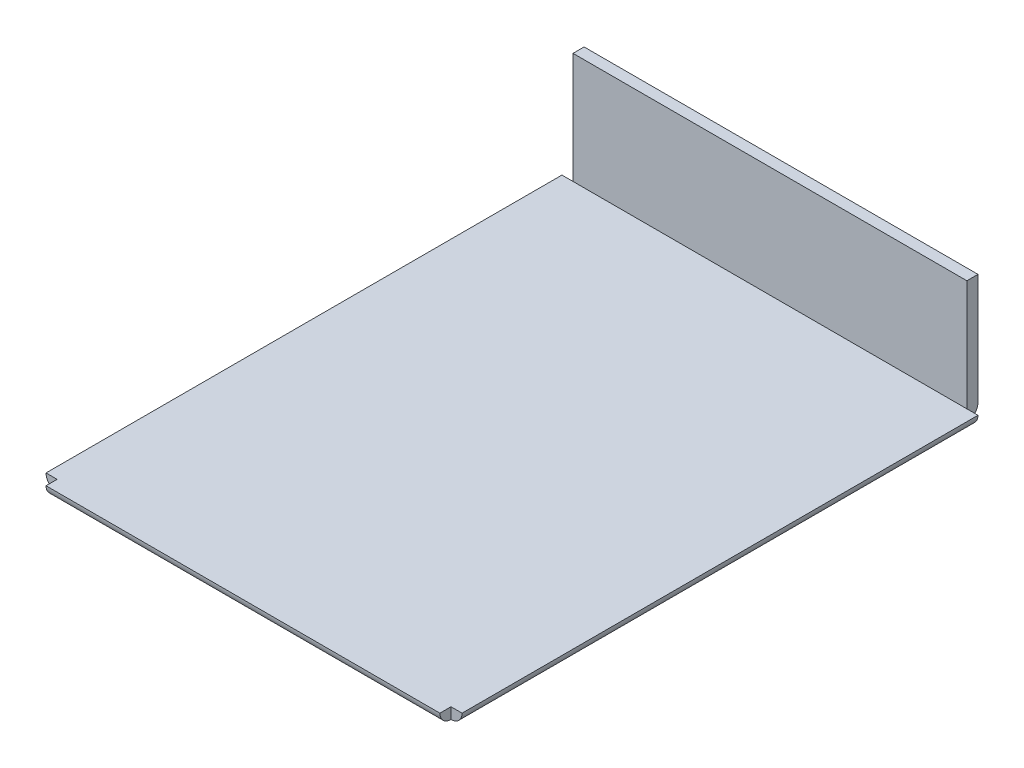
SolidWorks part; units mm, degrees
ref_plane "Front Plane" through (0, 0, 0) normal (0, 0, 1) x (1, 0, 0)
ref_plane "Top Plane" through (0, 0, 0) normal (0, 1, 0) x (1, 0, 0)
ref_plane "Right Plane" through (0, 0, 0) normal (1, 0, 0) x (0, 0, -1)
sketch "bottom side" plane through (0, 0, 0) normal (0, 1, 0) x (1, 0, 0)
  line L1 (0, 0) -> (71, 0)
  line L2 (0, 0) -> (0, 93)
  line L3 (0, 93) -> (71, 93)
  line L4 (71, 0) -> (71, 93)
  dimension "D1" = 71
  dimension "D2" = 93
extrude "bottom extr" add sketch "bottom side" along normal blind 2
sketch "X+ corner" plane through (71, 0, 0) normal (1, 0, 0) x (0, 0, -1)
  line L1 (0, 2) -> (93, 2)
  line L2 (0, 2) -> (0, 0)
  line L3 (0, 0) -> (93, 0)
  line L4 (93, 2) -> (93, 0)
revolve "X+ corner rev" add sketch "X+ corner" angle 90 about L1
sketch "Z+ corner" plane through (0, 0, 0) normal (0, 0, 1) x (1, 0, 0)
  line L0 (0, 2) -> (73, 2) construction
  line L1 (0, 0) -> (71, 0)
  line L2 (0, 0) -> (0, 2)
  line L3 (0, 2) -> (71, 2)
  line L4 (71, 0) -> (71, 2)
  dimension "D1" = 71
revolve "Z+ corner rev" add sketch "Z+ corner" angle 90 about L3
sketch "X0 corner" plane through (0, 0, 0) normal (-1, 0, 0) x (0, 0, 1)
  line L0 (-93, 2) -> (2, 2) construction
  line L1 (-93, 0) -> (0, 0)
  line L2 (-93, 0) -> (-93, 2)
  line L3 (-93, 2) -> (0, 2)
  line L4 (0, 0) -> (0, 2)
  dimension "D1" = 93
revolve "X0 corner rev" add sketch "X0 corner" angle 90 about L3
sketch "Z0 corner" plane through (0, 0, -93) normal (0, 0, -1) x (-1, 0, 0)
  line L0 (-73, 2) -> (2, 2) construction
  line L1 (-71, 0) -> (0, 0)
  line L2 (-71, 0) -> (-71, 2)
  line L3 (-71, 2) -> (0, 2)
  line L4 (0, 0) -> (0, 2)
revolve "Z0 corner rev" add sketch "Z0 corner" angle 90 about L3
sketch "Z0 side" plane through (0, 2, 0) normal (0, 1, 0) x (1, 0, 0)
  line L1 (71, 95) -> (0, 95)
  line L2 (71, 95) -> (71, 93)
  line L3 (71, 93) -> (0, 93)
  line L4 (0, 95) -> (0, 93)
extrude "Z0 extr" add sketch "Z0 side" along normal blind 20
